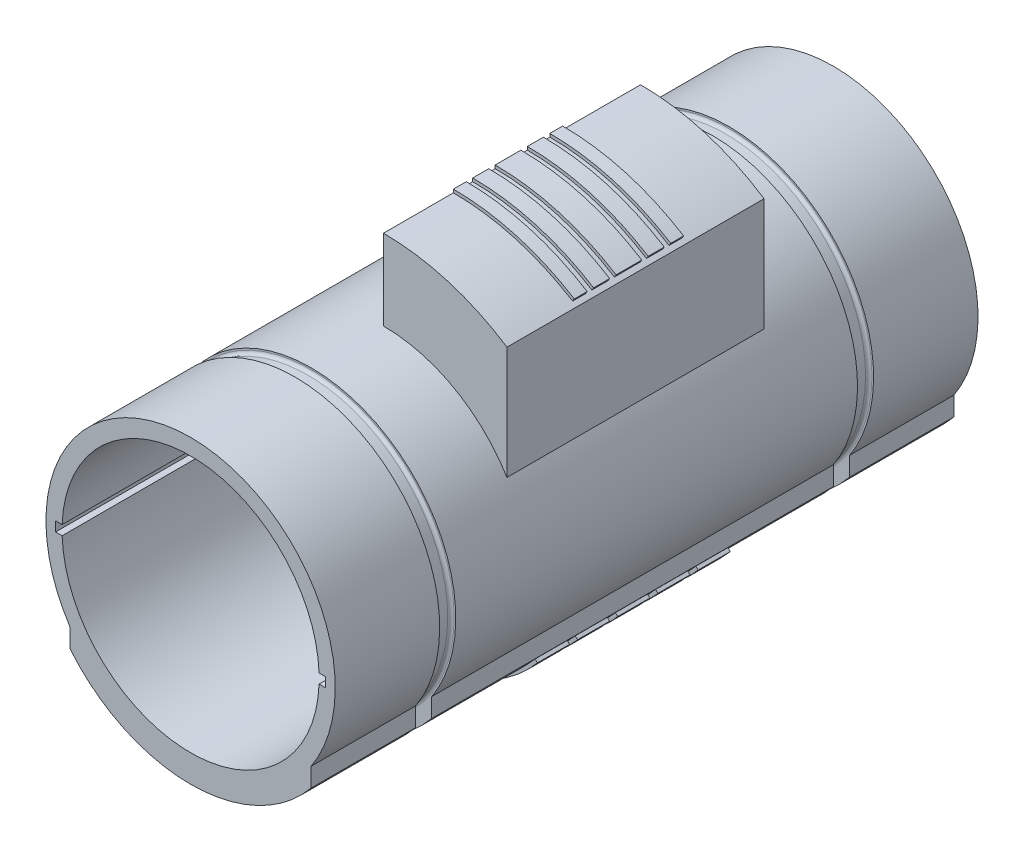
SolidWorks part; units mm, degrees
ref_plane "Plano frontal" through (0, 0, 0) normal (0, 0, 1) x (1, 0, 0)
ref_plane "Plano superior" through (0, 0, 0) normal (0, 1, 0) x (1, 0, 0)
ref_plane "Plano direito" through (0, 0, 0) normal (1, 0, 0) x (0, 0, -1)
sketch "Esboço1" plane through (0, 0, 0) normal (0, 0, 1) x (1, 0, 0)
  circle A0 centre (0, 0) radius 45
  dimension "D1" = 90
extrude "Ressalto-extrusão1" add sketch "Esboço1" along normal blind 200
sketch "Esboço2" plane through (0, 0, 0) normal (0, 0, 1) x (1, 0, 0)
  line L0 (0, 0) -> (0, -1.5)
  line L1 (0, -1.5) -> (42, -1.5)
  line L2 (42, -1.5) -> (42, 1.5)
  line L3 (42, 1.5) -> (-42, 1.5)
  line L4 (-42, 1.5) -> (-42, -1.5)
  line L5 (-42, -1.5) -> (0, -1.5)
  circle A0 centre (0, 0) radius 40
  circle A1 centre (0, 0) radius 45 construction
  dimension "D1" = 80
  dimension "D2" = 5
  dimension "D3" = 1.5
  dimension "D4" = 1.5
  dimension "D5" = 42
  dimension "D6" = 42
extrude "Corte-extrusão2" cut sketch "Esboço2" along normal blind 200
sketch "Esboço4" plane through (0, 0, 0) normal (0, 0, 1) x (1, 0, 0)
  line L2 (-37.5, -30.7571) -> (-37.5, -24.8747)
  line L3 (37.5, -30.7571) -> (37.5, -24.8747)
  arc A0 (-37.5, -30.7571) -> (37.5, -30.7571) centre (0, 0) ccw
  arc A1 (-34.7938, -28.5375) -> (34.7938, -28.5375) centre (0, 0) ccw
  circle A2 centre (0, 0) radius 45 construction
  circle A3 centre (0, 0) radius 45
  dimension "D1" = 75
  dimension "D2" = 3.5
extrude "Ressalto-extrusão2" add sketch "Esboço4" along normal blind 200 contours A3 L2 A0 L3 A1
sketch "Esboço6" plane through (0, 0, 0) normal (1, 0, 0) x (0, 0, -1)
  line L0 (-100, -48.5) -> (-95, -48.5)
  line L1 (-200, -48.5) -> (0, -48.5) construction
  line L2 (-100, -48.5) -> (-105, -48.5)
  line L3 (-95, -48.5) -> (-95, -49.5)
  line L4 (-95, -49.5) -> (-105, -49.5)
  line L5 (-105, -49.5) -> (-105, -48.5)
  line L6 (0, -48.5) -> (-3, -48.5)
  line L7 (-3, -48.5) -> (-3, -45.5)
  line L8 (-3, -45.5) -> (0, -45.5)
  line L9 (0, -48.5) -> (0, -30.7571) construction
  line L10 (0, -45.5) -> (0, -48.5)
  line L11 (-197, -48.5) -> (-200, -48.5)
  line L12 (-200, -48.5) -> (-200, -45.5)
  line L13 (-200, -45.5) -> (-197, -45.5)
  line L14 (-197, -45.5) -> (-197, -48.5)
  line L15 (-100, -48.5) -> (0, -48.5)
  line L16 (-50, -48.5) -> (-100, -48.5)
  line L17 (-50, -48.5) -> (-100, -48.5)
  line L18 (-75, -48.5) -> (-80, -48.5)
  line L19 (-75, -48.5) -> (-70, -48.5)
  line L20 (-70, -48.5) -> (-70, -49.5)
  line L21 (-70, -49.5) -> (-80, -49.5)
  line L22 (-80, -49.5) -> (-80, -48.5)
  line L23 (-100, -48.5) -> (-75, -48.5)
  line L24 (-100, -48.5) -> (-75, -48.5)
  line L25 (-100, -48.5) -> (-75, -48.5)
  line L26 (-87.5, -48.5) -> (-92.5, -48.5)
  line L27 (-92.5, -48.5) -> (-92.5, -49.5)
  line L28 (-92.5, -49.5) -> (-82.5, -49.5)
  line L29 (-82.5, -49.5) -> (-82.5, -48.5)
  line L30 (-82.5, -48.5) -> (-87.5, -48.5)
  line L31 (0, 0) -> (-217.2815, 0) construction
  line L32 (-107.5, -48.5) -> (-107.5, -49.5)
  line L33 (-107.5, -49.5) -> (-117.5, -49.5)
  line L34 (-117.5, -49.5) -> (-117.5, -48.5)
  line L35 (-130, -48.5) -> (-130, -49.5)
  line L36 (-130, -49.5) -> (-120, -49.5)
  line L37 (-120, -49.5) -> (-120, -48.5)
  line L38 (-107.5, -48.5) -> (-117.5, -48.5)
  line L39 (-120, -48.5) -> (-130, -48.5)
  dimension "D4" = 3
  dimension "D5" = 3
  dimension "D6" = 3
  dimension "D7" = 3
revolve "Revolução1" add sketch "Esboço6" angle 50 about L31 other way angle 50
sketch "Esboço7" plane through (0, 0, 0) normal (1, 0, 0) x (0, 0, -1)
  line L0 (-165, -48.5) -> (-162.5, -48.5)
  line L1 (-200, -48.5) -> (-130, -48.5) construction
  line L2 (-165, -48.5) -> (-167.5, -48.5)
  line L3 (-167.5, -48.5) -> (-167.5, -44.5)
  line L4 (-162.5, -47.1987) -> (-162.5, -48.5)
  line L5 (-166.5, -43.5) -> (-163.5, -43.5)
  line L6 (-162.5, -44.5) -> (-162.5, -47.1987)
  line L9 (-37.5, -48.5) -> (-37.5, -44.5)
  line L10 (-32.5, -47.1987) -> (-32.5, -48.5)
  line L11 (-36.5, -43.5) -> (-33.5, -43.5)
  line L12 (-32.5, -44.5) -> (-32.5, -47.1987)
  line L13 (-37.5, -48.5) -> (-32.5, -48.5)
  line L14 (0, 0) -> (-200, 0) construction
  line L15 (-200, 45) -> (-200, -24.8747) construction
  arc A0 (-33.5, -43.5) -> (-32.5, -44.5) centre (-33.5, -44.5) cw
  arc A1 (-37.5, -44.5) -> (-36.5, -43.5) centre (-36.5, -44.5) cw
  arc A2 (-163.5, -43.5) -> (-162.5, -44.5) centre (-163.5, -44.5) cw
  arc A3 (-167.5, -44.5) -> (-166.5, -43.5) centre (-166.5, -44.5) cw
  point P22 (-37.5, -43.5)
  point P27 (-167.5, -43.5)
  dimension "D4" = 1
  dimension "D1" = 2.5
  dimension "D2" = 2.5
  dimension "D3" = 5
  dimension "D6" = 5
revolve "Corte-Revolução3" cut sketch "Esboço7" angle 360 about L14
sketch "Esboço8" plane through (0, 0, 0) normal (1, 0, 0) x (0, 0, -1)
  line L0 (-100, 45) -> (-70, 45)
  line L1 (-37.5, 45) -> (-162.5, 45) construction
  line L2 (-100, 45) -> (-130, 45)
  line L3 (-70, 45) -> (-70, 60)
  line L4 (-70, 60) -> (-130, 60)
  line L5 (-130, 60) -> (-130, 45)
  line L6 (0, 0) -> (-200, -1.5) construction
  dimension "D1" = 15
ref_plane "Plano1" through (0, 0, 70) normal (0, 0, -1) x (-1, 0, 0)
sketch "Esboço13" plane through (0, 0, 70) normal (0, 0, -1) x (-1, 0, 0)
  line L0 (-39.9347, 20.7418) -> (-39.9347, 44.7797)
  line L1 (0, 45) -> (0, 60)
  arc A0 (0, 45) -> (-39.9347, 20.7418) centre (0, 0) ccw
  arc A1 (0, 60) -> (-39.9347, 44.7797) centre (0, 0) ccw
  arc A2 (0, 60) -> (-39.9347, 44.7797) centre (0, 0) ccw
  dimension "D1" = 120
sketch "Esboço16" plane through (0, 0, 0) normal (0, 0, 1) x (1, 0, 0)
  line L0 (0, 45) -> (0, 70)
  line L1 (42.826, 55.3709) -> (42.826, 13.8179)
  arc A0 (42.826, 55.3709) -> (0, 70) centre (0, 0) ccw
  arc A1 (37.5, -24.8747) -> (-37.5, -24.8747) centre (0, 0) ccw construction
  arc A2 (42.826, 13.8179) -> (0, 45) centre (0, 0) ccw
  dimension "D1" = 25
ref_plane "Plano2" through (0, 0, 100) normal (0, 0, -1) x (-1, 0, 0)
sketch "Esboço17" plane through (0, 0, 100) normal (0, 0, -1) x (-1, 0, 0)
  line L0 (0, 45) -> (0, 70)
  line L1 (-38.4318, 23.4094) -> (-38.4318, 58.5064)
  arc A0 (0, 70) -> (-38.4318, 58.5064) centre (0, 0) ccw
  arc A1 (37.5, -24.8747) -> (-37.5, -24.8747) centre (0, 0) ccw construction
  arc A2 (0, 45) -> (-38.4318, 23.4094) centre (0, 0) ccw
  dimension "D1" = 25
extrude "Ressalto-extrusão6" add sketch "Esboço17" along normal blind 40 and the other way blind 40
sketch "Esboço18" plane through (0, 0, 0) normal (1, 0, 0) x (0, 0, -1)
  line L0 (-77.5, 45) -> (-77.5, 65)
  line L1 (-140, 45) -> (-60, 45) construction
  line L2 (-77.5, 65) -> (-122.5, 65)
  line L3 (-122.5, 65) -> (-122.5, 45)
  line L4 (-140, 70) -> (-60, 70) construction
  line L5 (-100, 45) -> (-77.5, 45)
  line L6 (-100, 45) -> (-122.5, 45)
  line L7 (-60, 45) -> (-60, 70) construction
  line L8 (-140, 45) -> (-140, 70) construction
  line L9 (-100, 65) -> (-100, 45)
  line L10 (-100, 55) -> (-77.5, 55)
  line L11 (-100, 55) -> (-122.5, 55)
  circle A0 centre (-87, 55) radius 8
  circle A1 centre (-113, 55) radius 8
  dimension "D7" = 16
  dimension "D8" = 16
  dimension "D1" = 5
  dimension "D2" = 22.5
  dimension "D3" = 22.5
  dimension "D4" = 17.5
  dimension "D5" = 17.5
  dimension "D6" = 26
extrude "Corte-extrusão3" cut sketch "Esboço18" along normal blind 12 contours L10 A0 | L10 A0 | L11 A1 | L11 A1
ref_plane "Plano3" through (12, 0, 0) normal (-1, 0, 0) x (0, 0, 1)
sketch "Esboço19" plane through (12, 0, 0) normal (-1, 0, 0) x (0, 0, 1)
  line L0 (100, 45) -> (77.5, 45)
  line L1 (140, 45) -> (60, 45) construction
  line L2 (100, 45) -> (122.5, 45)
  line L3 (77.5, 45) -> (77.5, 65)
  line L4 (77.5, 65) -> (122.5, 65)
  line L5 (122.5, 65) -> (122.5, 45)
  dimension "D1" = 22.5
  dimension "D2" = 22.5
  dimension "D3" = 20
revolve "Corte-Revolução5" cut sketch "Esboço19" angle 180 about L0
sketch "Esboço20" plane through (0, 0, 0) normal (1, 0, 0) x (0, 0, -1)
  line L1 (-140, 70) -> (-60, 70) construction
  line L3 (-97.2424, 70) -> (-97.2424, 71)
  line L4 (-97.2424, 71) -> (-105.2424, 71)
  line L5 (-105.2424, 71) -> (-105.2424, 70)
  line L6 (-97.2424, 70) -> (-105.2424, 70)
  line L7 (-90.2424, 70) -> (-90.2424, 71)
  line L8 (-90.2424, 71) -> (-95.2424, 71)
  line L9 (-95.2424, 71) -> (-95.2424, 70)
  line L10 (-90.2424, 70) -> (-95.2424, 70)
  line L11 (-97.2424, 70) -> (-95.2424, 70)
  line L12 (-105.2424, 70) -> (-107.2424, 70)
  line L17 (-107.2424, 70) -> (-107.2424, 71)
  line L18 (-107.2424, 71) -> (-112.2424, 71)
  line L19 (-112.2424, 71) -> (-112.2424, 70)
  line L20 (-107.2424, 70) -> (-112.2424, 70)
  line L21 (-101.2424, 70) -> (-105.2424, 70)
  line L22 (-90.2424, 70) -> (-88.2424, 70)
  line L23 (-88.2424, 70) -> (-88.2424, 71)
  line L24 (-88.2424, 71) -> (-84.2424, 71)
  line L25 (-84.2424, 71) -> (-84.2424, 70)
  line L26 (-84.2424, 70) -> (-88.2424, 70)
  line L27 (-112.2424, 70) -> (-114.2424, 70)
  line L28 (-114.2424, 70) -> (-114.2424, 71)
  line L29 (-114.2424, 71) -> (-118.2424, 71)
  line L30 (-118.2424, 71) -> (-118.2424, 70)
  line L31 (-118.2424, 70) -> (-114.2424, 70)
  line L32 (0, 0) -> (-200, 0) construction
  line L33 (-200, 45) -> (-200, -24.8747) construction
  dimension "D1" = 2
  dimension "D2" = 2
  dimension "D3" = 8
  dimension "D4" = 2
  dimension "D5" = 5
  dimension "D6" = 4
  dimension "D7" = 5
  dimension "D8" = 2
  dimension "D9" = 4
revolve "Revolução3" add sketch "Esboço20" angle 32 about L32
sketch "Esboço21" plane through (0, 0, 0) normal (0, 0, 1) x (1, 0, 0)
  line L1 (42, 1.5) -> (39.9719, 1.5)
  line L2 (42, 1.5) -> (42, -1.5)
  line L3 (42, -1.5) -> (39.9719, -1.5)
  line L4 (39.9719, 1.5) -> (39.9719, -1.5)
  line L5 (-39.9719, 1.5) -> (-42, 1.5)
  line L6 (-39.9719, 1.5) -> (-39.9719, -1.5)
  line L7 (-39.9719, -1.5) -> (-42, -1.5)
  line L8 (-42, 1.5) -> (-42, -1.5)
extrude "Ressalto-extrusão8" add sketch "Esboço21" along normal blind 3
